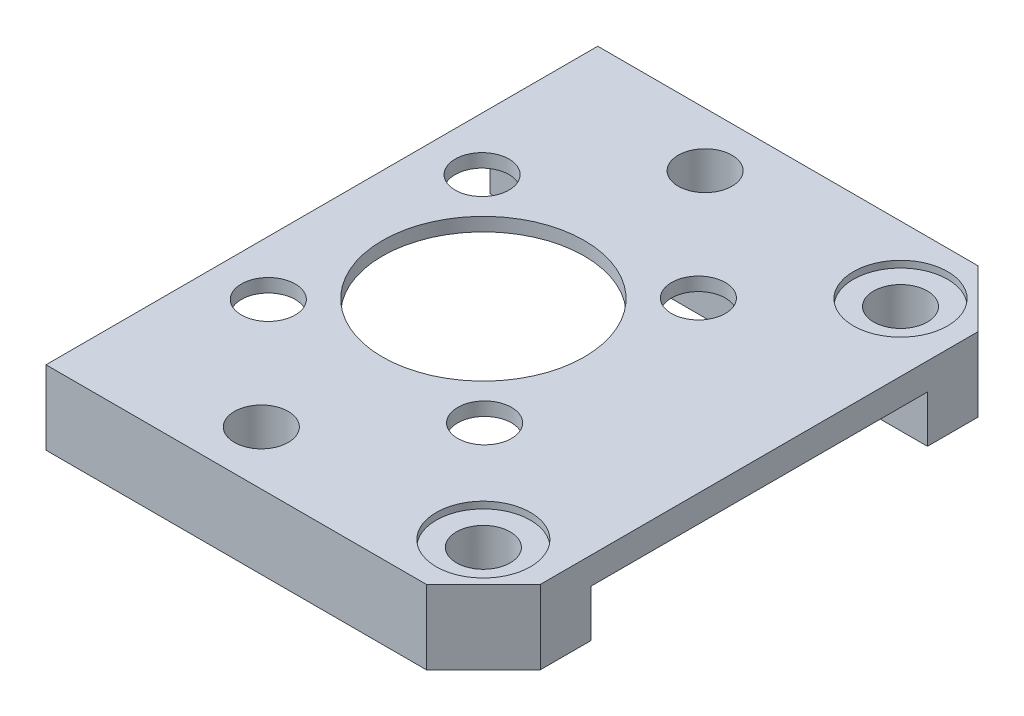
SolidWorks part; units mm, degrees
ref_plane "Front Plane" through (0, 0, 0) normal (0, 0, 1) x (1, 0, 0)
ref_plane "Top Plane" through (0, 0, 0) normal (0, 1, 0) x (1, 0, 0)
ref_plane "Right Plane" through (0, 0, 0) normal (1, 0, 0) x (0, 0, -1)
sketch "Sketch2" plane through (0, 0, 0) normal (0, 1, 0) x (1, 0, 0)
  line L1 (-20.5, -20.5) -> (20.5, -20.5)
  line L2 (-20.5, -20.5) -> (-20.5, 20.5)
  line L3 (-20.5, 20.5) -> (20.5, 20.5)
  line L4 (20.5, -20.5) -> (20.5, 20.5)
  line L5 (-20.5, -20.5) -> (20.5, 20.5) construction
  line L6 (-20.5, 20.5) -> (20.5, -20.5) construction
  point P0 (0, 0)
  dimension "D1" = 41
  dimension "D2" = 41
extrude "Boss-Extrude1" add sketch "Sketch2" along normal blind 2
sketch "Sketch3" plane through (0, 0, 0) normal (0, -1, 0) x (1, 0, 0)
  line L0 (-7.9432, -8.0372) -> (0, 0) construction
  line L5 (-7.9432, -8.0372) -> (7.9432, -8.0372) construction
  line L6 (-7.9432, -8.0372) -> (-7.9432, 8.0372) construction
  line L7 (-7.9432, 8.0372) -> (7.9432, 8.0372) construction
  line L8 (7.9432, -8.0372) -> (7.9432, 8.0372) construction
  line L9 (0, 0) -> (7.9432, 8.0372) construction
  line L10 (0, 0) -> (7.9432, -8.0372) construction
  line L11 (-7.9432, 8.0372) -> (0, 0) construction
  arc A1 (7.9432, 8.0372) -> (-7.9432, 8.0372) centre (0, 0) ccw construction
  arc A2 (-7.9432, -8.0372) -> (7.9432, -8.0372) centre (0, 0) ccw construction
  arc A3 (-7.9432, 8.0372) -> (-7.9432, -8.0372) centre (0, 0) ccw construction
  arc A4 (7.9432, -8.0372) -> (8.0686, 7.9112) centre (0, 0) ccw construction
  circle A5 centre (-7.9432, 8.0372) radius 2
  circle A10 centre (8.0372, 7.9432) radius 2
  circle A12 centre (7.9432, -8.0372) radius 2
  circle A13 centre (-8.0372, -7.9432) radius 2
  arc A14 (8.0686, 7.9112) -> (7.9432, 8.0372) centre (0, 0) ccw construction
  point P15 (-1.4144, -0.0142)
  point P19 (0, 0)
  dimension "D1" = 22.6
  dimension "D2" = 4
  dimension "D4" = 4
extrude "Cut-Extrude1" cut sketch "Sketch3" against normal through all
sketch "Sketch4" plane through (0, 2, 0) normal (0, 1, 0) x (1, 0, 0)
  circle A0 centre (0, 0) radius 7.5
  dimension "D1" = 15
extrude "Cut-Extrude2" cut sketch "Sketch4" against normal through all
sketch "Sketch5" plane through (0, 0, 0) normal (0, -1, 0) x (1, 0, 0)
  line L1 (-12.5, -12.5) -> (12.5, -12.5)
  line L2 (-12.5, -12.5) -> (-12.5, 12.5)
  line L3 (-12.5, 12.5) -> (12.5, 12.5)
  line L4 (12.5, -12.5) -> (12.5, 12.5)
  line L5 (-12.5, -12.5) -> (12.5, 12.5) construction
  line L6 (-12.5, 12.5) -> (12.5, -12.5) construction
  point P0 (0, 0)
  dimension "D1" = 25
  dimension "D2" = 25
extrude "Cut-Extrude3" cut sketch "Sketch5" against normal blind 1
sketch "Sketch6" plane through (0, 2, 0) normal (0, 1, 0) x (1, 0, 0)
  line L0 (-20.5, 16.2574) -> (-16.2574, 20.5)
  line L1 (-20.5, 20.5) -> (-20.5, -20.5) construction
  line L2 (20.5, 20.5) -> (-20.5, 20.5) construction
  line L4 (16.2574, 20.5) -> (20.5, 16.2574)
  line L5 (20.5, -20.5) -> (20.5, 20.5) construction
  line L7 (20.5, -16.2574) -> (16.2574, -20.5)
  line L8 (-20.5, -20.5) -> (20.5, -20.5) construction
  line L10 (-16.2574, -20.5) -> (-20.5, -16.2574)
  line L12 (-2.4898, 0) -> (5.6129, 0) construction
  line L13 (0, 5.0948) -> (0, 0) construction
  line L14 (0, 0) -> (3.8649, 3.8649) construction
  line L15 (-20.5, -16.2574) -> (-20.5, -20.5)
  line L16 (-20.5, -20.5) -> (-16.2574, -20.5)
  line L17 (16.2574, -20.5) -> (20.5, -20.5)
  line L18 (20.5, -20.5) -> (20.5, -16.2574)
  line L19 (20.5, 16.2574) -> (20.5, 20.5)
  line L20 (20.5, 20.5) -> (16.2574, 20.5)
  line L21 (-16.2574, 20.5) -> (-20.5, 20.5)
  line L22 (-20.5, 20.5) -> (-20.5, 16.2574)
  dimension "D1" = 6
  dimension "D2" = 6
  dimension "D3" = 45
  dimension "D4" = 6
  dimension "D5" = 6
extrude "Cut-Extrude4" cut sketch "Sketch6" against normal through all
sketch "Sketch7" plane through (0, 0, 0) normal (0, -1, 0) x (1, 0, 0)
  line L0 (-15.5, 15.5) -> (0, 0) construction
  line L1 (-15.5, -15.5) -> (15.5, -15.5) construction
  line L2 (-15.5, -15.5) -> (-15.5, 15.5) construction
  line L3 (-15.5, 15.5) -> (15.5, 15.5) construction
  line L4 (15.5, -15.5) -> (15.5, 15.5) construction
  line L5 (-15.5, -15.5) -> (0, 0) construction
  line L6 (0, 0) -> (15.5, -15.5) construction
  line L7 (0, 0) -> (15.5, 15.5) construction
  arc A0 (-15.5, -15.5) -> (15.5, -15.5) centre (0, 0) ccw construction
  arc A1 (-15.5, 15.5) -> (-15.5, -15.5) centre (0, 0) ccw construction
  arc A2 (15.5, -15.5) -> (15.5, 15.5) centre (0, 0) ccw construction
  arc A3 (15.5, 15.5) -> (-15.5, 15.5) centre (0, 0) ccw construction
  circle A4 centre (-15.5, 15.5) radius 2
  circle A5 centre (15.5, 15.5) radius 2
  circle A6 centre (15.5, -15.5) radius 2
  circle A7 centre (-15.5, -15.5) radius 2
  point P16 (0, 0)
  dimension "D2" = 4
  dimension "D4" = 31
  dimension "D3" = 4
extrude "Cut-Extrude5" cut sketch "Sketch7" against normal through all
sketch "Sketch8" plane through (0, 0, 0) normal (0, -1, 0) x (1, 0, 0)
  line L0 (-12.5, -12.5) -> (-12.5, 12.5) construction
  line L1 (-12.5, -12.5) -> (-20.477, -12.5) construction
  line L2 (-12.5, 12.5) -> (-20.477, 12.5) construction
  line L3 (-20.477, -12.5) -> (-20.477, 12.5) construction
  line L4 (12.5, -12.5) -> (12.5, 12.5) construction
  line L5 (12.5, -12.5) -> (20.4876, -12.5) construction
  line L6 (12.5, 12.5) -> (20.4876, 12.5) construction
  line L7 (20.4876, -12.5) -> (20.4876, 12.5) construction
  line L8 (-12.5, 12.5) -> (12.5, 12.5)
  line L9 (-12.5, 12.5) -> (-12.5, 20.5)
  line L10 (12.5, 12.5) -> (12.5, 20.5)
  line L11 (-12.5, 20.5) -> (12.5, 20.5)
  line L12 (12.5, -12.5) -> (-12.5, -12.5)
  line L13 (12.5, -12.5) -> (12.5, -20.4578)
  line L14 (-12.5, -12.5) -> (-12.5, -20.4578)
  line L15 (12.5, -20.4578) -> (-12.5, -20.4578)
  line L16 (-16.2574, 20.5) -> (16.2574, 20.5) construction
extrude "Boss-Extrude2" add sketch "Sketch8" along normal blind 3.5
sketch "Sketch9" plane through (0, -3.5, 0) normal (0, -1, 0) x (1, 0, 0)
  circle A0 centre (0, 16.5) radius 2
  circle A1 centre (0, -16.4789) radius 2
  dimension "D1" = 4
extrude "Cut-Extrude6" cut sketch "Sketch9" against normal through all
sketch "Sketch10" plane through (0, 0, 0) normal (0, -1, 0) x (1, 0, 0)
  line L0 (-20.5, -16.2574) -> (-16.2574, -20.5)
  line L1 (20.5, 12.5) -> (12.5, 12.5)
  line L2 (20.5, 12.5) -> (20.5, 16.2574)
  line L3 (16.2574, 20.5) -> (12.5, 20.5)
  line L4 (-20.5, 12.5) -> (-20.5, 16.2574)
  line L5 (-20.5, -12.5) -> (-12.5, -12.5)
  line L6 (-20.5, -12.5) -> (-20.5, -16.2574)
  line L8 (20.5, -12.5) -> (20.5, -16.2574)
  line L9 (-20.5, 16.2574) -> (-16.2574, 20.5)
  line L10 (16.2574, 20.5) -> (20.5, 16.2574)
  line L11 (20.5, -16.2574) -> (16.2574, -20.5)
  line L12 (-20.5, -12.5) -> (-20.5, -16.2574)
  line L13 (-12.5, 12.5) -> (-20.5, 12.5)
  line L14 (-12.5, 20.5) -> (-16.2574, 20.5)
  line L15 (12.5, -12.5) -> (20.5, -12.5)
  line L16 (-12.5, -12.5) -> (-12.5, 12.5)
  line L17 (-12.5, 12.5) -> (-12.5, 20.5)
  line L18 (-12.5, 20.5) -> (-16.2574, 20.5)
  line L19 (-16.2574, 20.5) -> (-20.5, 16.2574)
  line L20 (-20.5, 16.2574) -> (-20.5, -16.2574)
  line L21 (-20.5, -16.2574) -> (-16.2574, -20.5)
  line L22 (-16.2574, -20.5) -> (16.2574, -20.5)
  line L23 (16.2574, -20.5) -> (20.5, -16.2574)
  line L24 (20.5, -16.2574) -> (20.5, 16.2574)
  line L25 (20.5, 16.2574) -> (16.2574, 20.5)
  line L26 (16.2574, 20.5) -> (12.5, 20.5)
  line L27 (12.5, 20.5) -> (12.5, 12.5)
  line L28 (12.5, 12.5) -> (12.5, -12.5)
  line L29 (12.5, -12.5) -> (12.5, -20.4578)
  line L30 (12.5, -20.4578) -> (-12.5, -20.4578)
  line L31 (-12.5, -20.4578) -> (-12.5, -12.5)
  line L33 (-12.5, 12.5) -> (-12.5, 20.5)
  line L34 (-12.5, 20.5) -> (-16.2574, 20.5)
  line L35 (-16.2574, 20.5) -> (-20.5, 16.2574)
  line L36 (-20.5, 16.2574) -> (-20.5, 12.5)
  line L37 (-20.5, -16.2574) -> (-16.2574, -20.5)
  line L39 (16.2574, -20.5) -> (20.5, -16.2574)
  line L40 (20.5, -16.2574) -> (20.5, 16.2574)
  line L41 (20.5, 16.2574) -> (16.2574, 20.5)
  line L42 (16.2574, 20.5) -> (12.5, 20.5)
  line L43 (12.5, 20.5) -> (12.5, 12.5)
  line L44 (12.5, 12.5) -> (12.5, -12.5)
  line L45 (12.5, -12.5) -> (12.5, -20.4578)
  line L47 (-12.5, -20.4578) -> (-12.5, -12.5)
  line L50 (12.5, 20.5) -> (-12.5, 20.5) construction
  circle A0 centre (-15.5, 15.5) radius 2
  circle A1 centre (15.5, 15.5) radius 2
  circle A2 centre (15.5, -15.5) radius 2
  circle A3 centre (-15.5, -15.5) radius 2
  circle M19 centre (-15.5, -15.5) radius 2
  circle M20 centre (15.5, -15.5) radius 2
  circle M21 centre (15.5, 15.5) radius 2
  circle M22 centre (-15.5, 15.5) radius 2
  line M24 (-12.5, 12.5) -> (-12.5, 20.5)
  line M25 (-12.5, 20.5) -> (-16.2574, 20.5)
  line M26 (-16.2574, 20.5) -> (-20.5, 16.2574)
  line M27 (-20.5, 16.2574) -> (-20.5, -16.2574)
  line M28 (-20.5, -16.2574) -> (-16.2574, -20.5)
  line M29 (-16.2574, -20.5) -> (16.2574, -20.5)
  line M30 (16.2574, -20.5) -> (20.5, -16.2574)
  line M31 (20.5, -16.2574) -> (20.5, 16.2574)
  line M32 (20.5, 16.2574) -> (16.2574, 20.5)
  line M33 (16.2574, 20.5) -> (12.5, 20.5)
  line M34 (12.5, 20.5) -> (12.5, 12.5)
  line M36 (12.5, -12.5) -> (12.5, -20.4578)
  line M37 (12.5, -20.4578) -> (-12.5, -20.4578)
  line M38 (-12.5, -20.4578) -> (-12.5, -12.5)
  dimension "D1" = 0
extrude "Boss-Extrude3" add sketch "Sketch10" along normal up to surface (3.5 mm away) contours L13 M24 M25 M26 M27 M22 | L1 M31 M32 M33 M34 M21 | L15 L5 M36 M37 M38 M27 M28 M29 M30 M31 M19 M20 up to face at (0, -3.5, 14.5)
sketch "Sketch11" plane through (0, 2, 0) normal (0, 1, 0) x (1, 0, 0)
  circle A0 centre (-15.5, 15.5) radius 3.5
  circle A1 centre (15.5, 15.5) radius 3.5
  circle A2 centre (15.5, -15.5) radius 3.5
  circle A3 centre (-15.5, -15.5) radius 3.5
  point P12 (0, 0)
  dimension "D1" = 7
  dimension "D2" = 4
extrude "Cut-Extrude7" cut sketch "Sketch11" against normal offset from surface (3.5 mm away) 2 up to face at (0, -3.5, -18.4789)
sketch "Sketch12" plane through (0, 0, 0) normal (0, -1, 0) x (1, 0, 0)
  line L0 (-12.5, 12.5) -> (-12.5, -12.5) construction
  line L1 (-20.5, -12.5) -> (-12.5, -12.5)
  line L2 (-20.5, -12.5) -> (-20.5, -10.5)
  line L3 (-20.5, -10.5) -> (-12.5, -10.5)
  line L4 (-12.5, -12.5) -> (-12.5, -10.5)
  line L5 (-25.9518, 0) -> (26.3784, 0) construction
  line L6 (0, 23.4974) -> (0, -23.7021) construction
  line L7 (-12.5, 12.5) -> (-12.5, 10.5)
  line L8 (-20.5, 12.5) -> (-12.5, 12.5)
  line L9 (-20.5, 12.5) -> (-20.5, 10.5)
  line L10 (-20.5, 10.5) -> (-12.5, 10.5)
  line L11 (12.5, -12.5) -> (12.5, -10.5)
  line L12 (20.5, -10.5) -> (12.5, -10.5)
  line L13 (20.5, -12.5) -> (20.5, -10.5)
  line L14 (20.5, -12.5) -> (12.5, -12.5)
  line L15 (20.5, 10.5) -> (12.5, 10.5)
  line L16 (20.5, 12.5) -> (20.5, 10.5)
  line L17 (20.5, 12.5) -> (12.5, 12.5)
  line L18 (12.5, 12.5) -> (12.5, 10.5)
  dimension "D1" = 2
extrude "Boss-Extrude4" add sketch "Sketch12" along normal up to surface (3.5 mm away) up to face at (0, -3.5, 14.5)
sketch "Sketch13" plane through (0, 2, 0) normal (0, 1, 0) x (1, 0, 0)
  circle A0 centre (-15.5, 15.5) radius 3.5
  circle A1 centre (15.5, 15.5) radius 3.5
  circle A2 centre (15.5, -15.5) radius 3.5
  circle A3 centre (-15.5, -15.5) radius 3.5
  point P12 (0, 0)
  dimension "D1" = 4
extrude "Cut-Extrude8" cut sketch "Sketch13" against normal up to surface (3.5 mm away) up to face at (-15.5, -1.5, -13.5)
sketch "Sketch14" plane through (0, -1.5, 0) normal (0, 1, 0) x (1, 0, 0)
  circle A0 centre (-15.5, -15.5) radius 2
  circle A1 centre (-15.5, -15.5) radius 3.5
  circle A2 centre (-15.5, 15.5) radius 3.5
  circle A3 centre (-15.5, 15.5) radius 2
  circle A4 centre (15.5, 15.5) radius 3.5
  circle A5 centre (15.5, 15.5) radius 2
  circle A6 centre (15.5, -15.5) radius 3.5
  circle A7 centre (15.5, -15.5) radius 2
  point P16 (0, 0)
  dimension "D1" = 4
extrude "Boss-Extrude5" add sketch "Sketch14" along normal offset from surface (3 mm away) 0.5 up to face at (-15.5, 2, 19)
sketch "Sketch15" plane through (0, 2, 0) normal (0, 1, 0) x (1, 0, 0)
  line L0 (0, 20.5) -> (0, -20.5) construction
  line L1 (16.2574, 20.5) -> (-16.2574, 20.5) construction
  line L2 (-16.2574, -20.5) -> (16.2574, -20.5) construction
  line L3 (0, -16.5) -> (8, -16.5) construction
  line L4 (0, -16.5) -> (-8, -16.5) construction
  line L5 (0, 16.4789) -> (8, 16.4789) construction
  line L6 (0, 16.4789) -> (-8, 16.4789) construction
  line L7 (-8, 20.5) -> (-8, 16.4789) construction
  line L8 (-8, 16.4789) -> (-8, 12.4578) construction
  line L9 (-8, -20.5) -> (-8, -16.5) construction
  line L10 (-8, -16.5) -> (-8, -12.5) construction
  line L11 (-3.025, 0) -> (3.025, 0) construction
  line L12 (8, 12.4578) -> (-8, 12.4578)
  line L13 (8, 12.4578) -> (8, 20.5)
  line L14 (8, 20.5) -> (-8, 20.5)
  line L15 (-8, 12.4578) -> (-8, 20.5)
  line L16 (8, -12.5) -> (-8, -12.5)
  line L17 (8, -12.5) -> (8, -20.5)
  line L18 (8, -20.5) -> (-8, -20.5)
  line L19 (-8, -12.5) -> (-8, -20.5)
  circle A0 centre (0, 16.4789) radius 2
  circle A1 centre (0, -16.4789) radius 2
  dimension "D1" = 8
extrude "Boss-Extrude6" add sketch "Sketch15" along normal blind 4
sketch "Sketch16" plane through (0, -3.5, 0) normal (0, -1, 0) x (1, 0, 0)
  line L0 (-20.5, 10.5) -> (-20.5, 16.2574) construction
  line L1 (-12.5, -12.5) -> (-20.5, -12.5)
  line L2 (-12.5, -12.5) -> (-12.5, 12.5)
  line L3 (-12.5, 12.5) -> (-20.5, 12.5)
  line L4 (-20.5, -12.5) -> (-20.5, 12.5)
  line L5 (12.5, 12.5) -> (20.5, 12.5)
  line L6 (12.5, 12.5) -> (12.5, -12.5)
  line L7 (20.5, 12.5) -> (20.5, -12.5)
  line L8 (12.5, -12.5) -> (20.5, -12.5)
  line L9 (20.5, 16.2574) -> (20.5, 10.5) construction
extrude "Cut-Extrude9" cut sketch "Sketch16" against normal up to surface (3.5 mm away) up to face at (16.5, 0, 0)
sketch "Sketch18" plane through (0, 6, 0) normal (0, 1, 0) x (1, 0, 0)
  line L1 (-16.2574, -20.5) -> (16.2574, -20.5)
  line L2 (-16.2574, -20.5) -> (-16.2574, 20.5)
  line L3 (-16.2574, 20.5) -> (16.2574, 20.5)
  line L4 (16.2574, -20.5) -> (16.2574, 20.5)
  line L5 (-16.2574, -20.5) -> (16.2574, 20.5) construction
  line L6 (-16.2574, 20.5) -> (16.2574, -20.5) construction
  point P0 (0, 0)
extrude "Cut-Extrude10" cut sketch "Sketch18" against normal up to surface (4 mm away) up to face at (0, 2, 0.0053)
sketch "Sketch19" plane through (0, 2, 0) normal (0, 1, 0) x (1, 0, 0)
  line L0 (-12, 20.5) -> (-12, -20.5)
  line L8 (20.5, 16.2574) -> (16.2574, 20.5)
  line L9 (16.2574, 20.5) -> (-16.2574, 20.5)
  line L10 (-16.2574, 20.5) -> (-20.5, 16.2574)
  line L11 (-20.5, 16.2574) -> (-20.5, -16.2574)
  line L12 (-20.5, -16.2574) -> (-16.2574, -20.5)
  line L13 (-16.2574, -20.5) -> (16.2574, -20.5)
  line L14 (16.2574, -20.5) -> (20.5, -16.2574)
  line L15 (20.5, -16.2574) -> (20.5, 16.2574)
  line L17 (-12, 20.5) -> (-16.2574, 20.5)
  line L18 (-16.2574, 20.5) -> (-20.5, 16.2574)
  line L19 (-20.5, 16.2574) -> (-20.5, -16.2574)
  line L20 (-20.5, -16.2574) -> (-16.2574, -20.5)
  line L21 (-16.2574, -20.5) -> (-12, -20.5)
  dimension "D1" = 0
extrude "Cut-Extrude12" cut sketch "Sketch19" against normal through all
